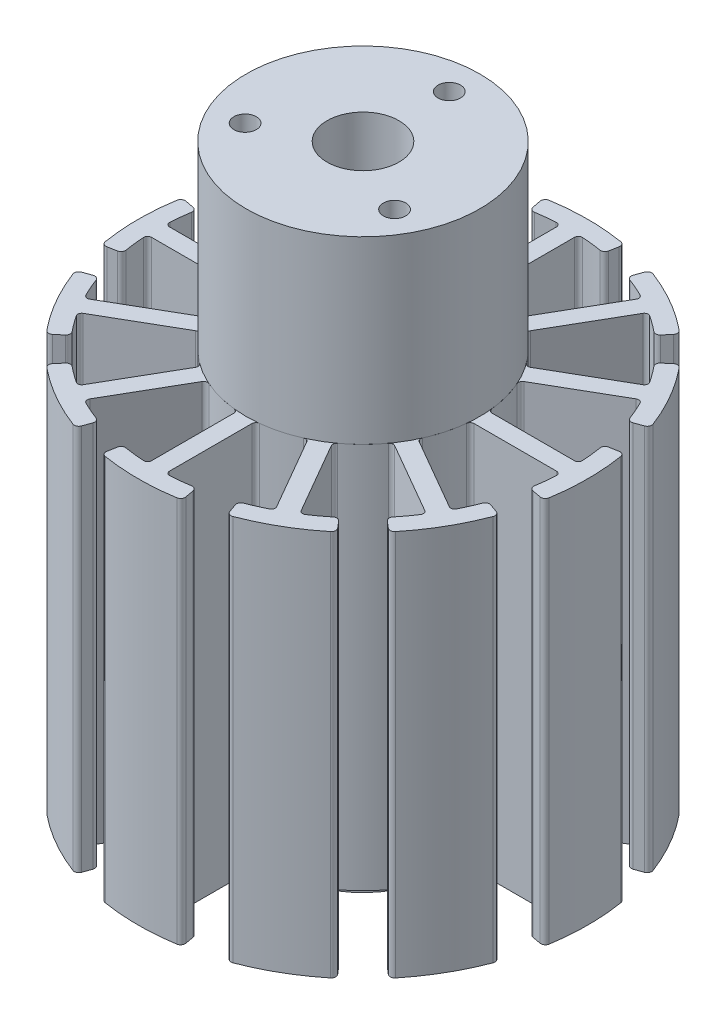
SolidWorks part; units mm, degrees
ref_plane "Front Plane" through (0, 0, 0) normal (0, 0, 1) x (1, 0, 0)
ref_plane "Top Plane" through (0, 0, 0) normal (0, 1, 0) x (1, 0, 0)
ref_plane "Right Plane" through (0, 0, 0) normal (1, 0, 0) x (0, 0, -1)
sketch "Sketch1" plane through (0, 0, 0) normal (0, 1, 0) x (1, 0, 0)
  circle A0 centre (0, 0) radius 13
  dimension "D1" = 26
extrude "Boss-Extrude1" add sketch "Sketch1" along normal blind 20
sketch "Sketch2" plane through (0, 20, 0) normal (0, 1, 0) x (1, 0, 0)
  line L0 (0, 0) -> (0, 11.9477) construction
  circle A0 centre (0, 9.6) radius 1.25
  circle A1 centre (8.3138, -4.8) radius 1.25
  circle A2 centre (-8.3138, -4.8) radius 1.25
  point P12 (0, 0)
  dimension "D1" = 9.6
  dimension "D2" = 3
extrude "Cut-Extrude1" cut sketch "Sketch2" against normal blind 5
sketch "Sketch4" plane through (0, 0, 0) normal (0, -1, 0) x (1, 0, 0)
  line L6 (0, 13) -> (0, 25) construction
  line L12 (1, 13.3636) -> (1, 22.5128)
  line L13 (-1, 13.3636) -> (-1, 22.5128)
  line L15 (4.3912, 24.0981) -> (4.2119, 23.1141)
  line L17 (-4.3912, 24.0981) -> (-4.2119, 23.1141)
  line L18 (4.1232, 22.6274) -> (4.4817, 24.595) construction
  line L19 (-4.1232, 22.6274) -> (-4.4817, 24.595) construction
  line L20 (15.8519, 18.674) -> (15.2046, 17.9114)
  line L21 (8.2462, 23.0651) -> (7.9094, 22.1233)
  line L22 (14.8845, 17.5343) -> (16.1788, 19.059) construction
  line L23 (7.7429, 21.6575) -> (8.4162, 23.5408) construction
  line L24 (7.5478, 11.0732) -> (12.1224, 18.9967)
  line L25 (5.8158, 12.0732) -> (10.3904, 19.9967)
  line L26 (23.0651, 8.2462) -> (22.1233, 7.9094)
  line L27 (18.674, 15.8519) -> (17.9114, 15.2046)
  line L28 (21.6575, 7.7429) -> (23.5408, 8.4162) construction
  line L29 (17.5343, 14.8845) -> (19.059, 16.1788) construction
  line L30 (12.0732, 5.8158) -> (19.9967, 10.3904)
  line L31 (11.0732, 7.5478) -> (18.9967, 12.1224)
  line L32 (24.0981, -4.3912) -> (23.1141, -4.2119)
  line L33 (24.0981, 4.3912) -> (23.1141, 4.2119)
  line L34 (22.6274, -4.1232) -> (24.595, -4.4817) construction
  line L35 (22.6274, 4.1232) -> (24.595, 4.4817) construction
  line L36 (13.3636, -1) -> (22.5128, -1)
  line L37 (13.3636, 1) -> (22.5128, 1)
  line L38 (18.674, -15.8519) -> (17.9114, -15.2046)
  line L39 (23.0651, -8.2462) -> (22.1233, -7.9094)
  line L40 (17.5343, -14.8845) -> (19.059, -16.1788) construction
  line L41 (21.6575, -7.7429) -> (23.5408, -8.4162) construction
  line L42 (11.0732, -7.5478) -> (18.9967, -12.1224)
  line L43 (12.0732, -5.8158) -> (19.9967, -10.3904)
  line L44 (8.2462, -23.0651) -> (7.9094, -22.1233)
  line L45 (15.8519, -18.674) -> (15.2046, -17.9114)
  line L46 (7.7429, -21.6575) -> (8.4162, -23.5408) construction
  line L47 (14.8845, -17.5343) -> (16.1788, -19.059) construction
  line L48 (5.8158, -12.0732) -> (10.3904, -19.9967)
  line L49 (7.5478, -11.0732) -> (12.1224, -18.9967)
  line L50 (-4.3912, -24.0981) -> (-4.2119, -23.1141)
  line L51 (4.3912, -24.0981) -> (4.2119, -23.1141)
  line L52 (-4.1232, -22.6274) -> (-4.4817, -24.595) construction
  line L53 (4.1232, -22.6274) -> (4.4817, -24.595) construction
  line L54 (-1, -13.3636) -> (-1, -22.5128)
  line L55 (1, -13.3636) -> (1, -22.5128)
  line L56 (-15.8519, -18.674) -> (-15.2046, -17.9114)
  line L57 (-8.2462, -23.0651) -> (-7.9094, -22.1233)
  line L58 (-14.8845, -17.5343) -> (-16.1788, -19.059) construction
  line L59 (-7.7429, -21.6575) -> (-8.4162, -23.5408) construction
  line L60 (-7.5478, -11.0732) -> (-12.1224, -18.9967)
  line L61 (-5.8158, -12.0732) -> (-10.3904, -19.9967)
  line L62 (-23.0651, -8.2462) -> (-22.1233, -7.9094)
  line L63 (-18.674, -15.8519) -> (-17.9114, -15.2046)
  line L64 (-21.6575, -7.7429) -> (-23.5408, -8.4162) construction
  line L65 (-17.5343, -14.8845) -> (-19.059, -16.1788) construction
  line L66 (-12.0732, -5.8158) -> (-19.9967, -10.3904)
  line L67 (-11.0732, -7.5478) -> (-18.9967, -12.1224)
  line L68 (-24.0981, 4.3912) -> (-23.1141, 4.2119)
  line L69 (-24.0981, -4.3912) -> (-23.1141, -4.2119)
  line L70 (-22.6274, 4.1232) -> (-24.595, 4.4817) construction
  line L71 (-22.6274, -4.1232) -> (-24.595, -4.4817) construction
  line L72 (-13.3636, 1) -> (-22.5128, 1)
  line L73 (-13.3636, -1) -> (-22.5128, -1)
  line L74 (-18.674, 15.8519) -> (-17.9114, 15.2046)
  line L75 (-23.0651, 8.2462) -> (-22.1233, 7.9094)
  line L76 (-17.5343, 14.8845) -> (-19.059, 16.1788) construction
  line L77 (-21.6575, 7.7429) -> (-23.5408, 8.4162) construction
  line L78 (-11.0732, 7.5478) -> (-18.9967, 12.1224)
  line L79 (-12.0732, 5.8158) -> (-19.9967, 10.3904)
  line L80 (-8.2462, 23.0651) -> (-7.9094, 22.1233)
  line L81 (-15.8519, 18.674) -> (-15.2046, 17.9114)
  line L82 (-7.7429, 21.6575) -> (-8.4162, 23.5408) construction
  line L83 (-14.8845, 17.5343) -> (-16.1788, 19.059) construction
  line L84 (-5.8158, 12.0732) -> (-10.3904, 19.9967)
  line L85 (-7.5478, 11.0732) -> (-12.1224, 18.9967)
  arc A0 (3.9789, 24.6813) -> (-3.9789, 24.6813) centre (0, 0) ccw
  arc A1 (3.6408, 22.71) -> (1.4693, 22.953) centre (0, 0) ccw
  arc A2 (-1.3938, 12.9251) -> (-5.2555, 11.8903) centre (0, 0) ccw
  circle A3 centre (0, 0) radius 13 construction
  arc A4 (-12.7489, 19.1433) -> (-14.8845, 17.5343) centre (0, 0) ccw
  arc A5 (-12.5, 21.6506) -> (-16.1788, 19.059) centre (0, 0) ccw
  arc A6 (-4.3912, 24.0981) -> (-3.9789, 24.6813) centre (-3.8993, 24.1877) cw
  arc A7 (-4.2119, 23.1141) -> (-3.6408, 22.71) centre (-3.72, 23.2037) ccw
  arc A8 (4.2119, 23.1141) -> (3.6408, 22.71) centre (3.72, 23.2037) cw
  arc A9 (3.9789, 24.6813) -> (4.3912, 24.0981) centre (3.8993, 24.1877) cw
  arc A10 (-1.4693, 22.953) -> (-3.6408, 22.71) centre (0, 0) ccw
  arc A11 (-1, 22.5128) -> (-1.4693, 22.953) centre (-1.4411, 22.5128) ccw
  arc A12 (1, 22.5128) -> (1.4693, 22.953) centre (1.4411, 22.5128) cw
  arc A13 (-1, 13.3636) -> (-1.3938, 12.9251) centre (-1.4411, 13.3636) cw
  arc A14 (1, 13.3636) -> (1.3938, 12.9251) centre (1.4411, 13.3636) ccw
  arc A15 (5.2555, 11.8903) -> (-5.2555, 11.8903) centre (0, 0) ccw
  arc A16 (15.7865, 19.3852) -> (8.8949, 23.3641) centre (0, 0) ccw
  arc A17 (14.5081, 17.847) -> (12.7489, 19.1433) centre (0, 0) ccw
  arc A18 (8.2462, 23.0651) -> (8.8949, 23.3641) centre (8.717, 22.8968) cw
  arc A19 (7.9094, 22.1233) -> (8.202, 21.4879) centre (8.3803, 21.955) ccw
  arc A20 (15.2046, 17.9114) -> (14.5081, 17.847) centre (14.8234, 18.235) cw
  arc A21 (15.7865, 19.3852) -> (15.8519, 18.674) centre (15.4707, 18.9975) cw
  arc A22 (10.2041, 20.6125) -> (8.202, 21.4879) centre (0, 0) ccw
  arc A23 (10.3904, 19.9967) -> (10.2041, 20.6125) centre (10.0084, 20.2172) ccw
  arc A24 (12.1224, 18.9967) -> (12.7489, 19.1433) centre (12.5044, 18.7761) cw
  arc A25 (5.8158, 12.0732) -> (5.2555, 11.8903) centre (5.4338, 12.2938) cw
  arc A26 (23.3641, 8.8949) -> (19.3852, 15.7865) centre (0, 0) ccw
  arc A27 (21.4879, 8.202) -> (20.6125, 10.2041) centre (0, 0) ccw
  arc A28 (18.674, 15.8519) -> (19.3852, 15.7865) centre (18.9975, 15.4707) cw
  arc A29 (17.9114, 15.2046) -> (17.847, 14.5081) centre (18.235, 14.8234) ccw
  arc A30 (22.1233, 7.9094) -> (21.4879, 8.202) centre (21.955, 8.3803) cw
  arc A31 (23.3641, 8.8949) -> (23.0651, 8.2462) centre (22.8968, 8.717) cw
  arc A32 (19.1433, 12.7489) -> (17.847, 14.5081) centre (0, 0) ccw
  arc A33 (18.9967, 12.1224) -> (19.1433, 12.7489) centre (18.7761, 12.5044) ccw
  arc A34 (19.9967, 10.3904) -> (20.6125, 10.2041) centre (20.2172, 10.0084) cw
  arc A35 (11.0732, 7.5478) -> (10.4965, 7.6696) centre (10.8527, 7.9298) cw
  arc A36 (24.6813, -3.9789) -> (24.6813, 3.9789) centre (0, 0) ccw
  arc A37 (22.71, -3.6408) -> (22.953, -1.4693) centre (0, 0) ccw
  arc A38 (24.0981, 4.3912) -> (24.6813, 3.9789) centre (24.1877, 3.8993) cw
  arc A39 (23.1141, 4.2119) -> (22.71, 3.6408) centre (23.2037, 3.72) ccw
  arc A40 (23.1141, -4.2119) -> (22.71, -3.6408) centre (23.2037, -3.72) cw
  arc A41 (24.6813, -3.9789) -> (24.0981, -4.3912) centre (24.1877, -3.8993) cw
  arc A42 (22.953, 1.4693) -> (22.71, 3.6408) centre (0, 0) ccw
  arc A43 (22.5128, 1) -> (22.953, 1.4693) centre (22.5128, 1.4411) ccw
  arc A44 (22.5128, -1) -> (22.953, -1.4693) centre (22.5128, -1.4411) cw
  arc A45 (13.3636, 1) -> (12.9251, 1.3938) centre (13.3636, 1.4411) cw
  arc A46 (19.3852, -15.7865) -> (23.3641, -8.8949) centre (0, 0) ccw
  arc A47 (17.847, -14.5081) -> (19.1433, -12.7489) centre (0, 0) ccw
  arc A48 (23.0651, -8.2462) -> (23.3641, -8.8949) centre (22.8968, -8.717) cw
  arc A49 (22.1233, -7.9094) -> (21.4879, -8.202) centre (21.955, -8.3803) ccw
  arc A50 (17.9114, -15.2046) -> (17.847, -14.5081) centre (18.235, -14.8234) cw
  arc A51 (19.3852, -15.7865) -> (18.674, -15.8519) centre (18.9975, -15.4707) cw
  arc A52 (20.6125, -10.2041) -> (21.4879, -8.202) centre (0, 0) ccw
  arc A53 (19.9967, -10.3904) -> (20.6125, -10.2041) centre (20.2172, -10.0084) ccw
  arc A54 (18.9967, -12.1224) -> (19.1433, -12.7489) centre (18.7761, -12.5044) cw
  arc A55 (12.0732, -5.8158) -> (11.8903, -5.2555) centre (12.2938, -5.4338) cw
  arc A56 (8.8949, -23.3641) -> (15.7865, -19.3852) centre (0, 0) ccw
  arc A57 (8.202, -21.4879) -> (10.2041, -20.6125) centre (0, 0) ccw
  arc A58 (15.8519, -18.674) -> (15.7865, -19.3852) centre (15.4707, -18.9975) cw
  arc A59 (15.2046, -17.9114) -> (14.5081, -17.847) centre (14.8234, -18.235) ccw
  arc A60 (7.9094, -22.1233) -> (8.202, -21.4879) centre (8.3803, -21.955) cw
  arc A61 (8.8949, -23.3641) -> (8.2462, -23.0651) centre (8.717, -22.8968) cw
  arc A62 (12.7489, -19.1433) -> (14.5081, -17.847) centre (0, 0) ccw
  arc A63 (12.1224, -18.9967) -> (12.7489, -19.1433) centre (12.5044, -18.7761) ccw
  arc A64 (10.3904, -19.9967) -> (10.2041, -20.6125) centre (10.0084, -20.2172) cw
  arc A65 (7.5478, -11.0732) -> (7.6696, -10.4965) centre (7.9298, -10.8527) cw
  arc A66 (-3.9789, -24.6813) -> (3.9789, -24.6813) centre (0, 0) ccw
  arc A67 (-3.6408, -22.71) -> (-1.4693, -22.953) centre (0, 0) ccw
  arc A68 (4.3912, -24.0981) -> (3.9789, -24.6813) centre (3.8993, -24.1877) cw
  arc A69 (4.2119, -23.1141) -> (3.6408, -22.71) centre (3.72, -23.2037) ccw
  arc A70 (-4.2119, -23.1141) -> (-3.6408, -22.71) centre (-3.72, -23.2037) cw
  arc A71 (-3.9789, -24.6813) -> (-4.3912, -24.0981) centre (-3.8993, -24.1877) cw
  arc A72 (1.4693, -22.953) -> (3.6408, -22.71) centre (0, 0) ccw
  arc A73 (1, -22.5128) -> (1.4693, -22.953) centre (1.4411, -22.5128) ccw
  arc A74 (-1, -22.5128) -> (-1.4693, -22.953) centre (-1.4411, -22.5128) cw
  arc A75 (1, -13.3636) -> (1.3938, -12.9251) centre (1.4411, -13.3636) cw
  arc A76 (-15.7865, -19.3852) -> (-8.8949, -23.3641) centre (0, 0) ccw
  arc A77 (-14.5081, -17.847) -> (-12.7489, -19.1433) centre (0, 0) ccw
  arc A78 (-8.2462, -23.0651) -> (-8.8949, -23.3641) centre (-8.717, -22.8968) cw
  arc A79 (-7.9094, -22.1233) -> (-8.202, -21.4879) centre (-8.3803, -21.955) ccw
  arc A80 (-15.2046, -17.9114) -> (-14.5081, -17.847) centre (-14.8234, -18.235) cw
  arc A81 (-15.7865, -19.3852) -> (-15.8519, -18.674) centre (-15.4707, -18.9975) cw
  arc A82 (-10.2041, -20.6125) -> (-8.202, -21.4879) centre (0, 0) ccw
  arc A83 (-10.3904, -19.9967) -> (-10.2041, -20.6125) centre (-10.0084, -20.2172) ccw
  arc A84 (-12.1224, -18.9967) -> (-12.7489, -19.1433) centre (-12.5044, -18.7761) cw
  arc A85 (-5.8158, -12.0732) -> (-5.2555, -11.8903) centre (-5.4338, -12.2938) cw
  arc A86 (-23.3641, -8.8949) -> (-19.3852, -15.7865) centre (0, 0) ccw
  arc A87 (-21.4879, -8.202) -> (-20.6125, -10.2041) centre (0, 0) ccw
  arc A88 (-18.674, -15.8519) -> (-19.3852, -15.7865) centre (-18.9975, -15.4707) cw
  arc A89 (-17.9114, -15.2046) -> (-17.847, -14.5081) centre (-18.235, -14.8234) ccw
  arc A90 (-22.1233, -7.9094) -> (-21.4879, -8.202) centre (-21.955, -8.3803) cw
  arc A91 (-23.3641, -8.8949) -> (-23.0651, -8.2462) centre (-22.8968, -8.717) cw
  arc A92 (-19.1433, -12.7489) -> (-17.847, -14.5081) centre (0, 0) ccw
  arc A93 (-18.9967, -12.1224) -> (-19.1433, -12.7489) centre (-18.7761, -12.5044) ccw
  arc A94 (-19.9967, -10.3904) -> (-20.6125, -10.2041) centre (-20.2172, -10.0084) cw
  arc A95 (-11.0732, -7.5478) -> (-10.4965, -7.6696) centre (-10.8527, -7.9298) cw
  arc A96 (-24.6813, 3.9789) -> (-24.6813, -3.9789) centre (0, 0) ccw
  arc A97 (-22.71, 3.6408) -> (-22.953, 1.4693) centre (0, 0) ccw
  arc A98 (-24.0981, -4.3912) -> (-24.6813, -3.9789) centre (-24.1877, -3.8993) cw
  arc A99 (-23.1141, -4.2119) -> (-22.71, -3.6408) centre (-23.2037, -3.72) ccw
  arc A100 (-23.1141, 4.2119) -> (-22.71, 3.6408) centre (-23.2037, 3.72) cw
  arc A101 (-24.6813, 3.9789) -> (-24.0981, 4.3912) centre (-24.1877, 3.8993) cw
  arc A102 (-22.953, -1.4693) -> (-22.71, -3.6408) centre (0, 0) ccw
  arc A103 (-22.5128, -1) -> (-22.953, -1.4693) centre (-22.5128, -1.4411) ccw
  arc A104 (-22.5128, 1) -> (-22.953, 1.4693) centre (-22.5128, 1.4411) cw
  arc A105 (-13.3636, -1) -> (-12.9251, -1.3938) centre (-13.3636, -1.4411) cw
  arc A106 (-19.3852, 15.7865) -> (-23.3641, 8.8949) centre (0, 0) ccw
  arc A107 (-17.847, 14.5081) -> (-19.1433, 12.7489) centre (0, 0) ccw
  arc A108 (-23.0651, 8.2462) -> (-23.3641, 8.8949) centre (-22.8968, 8.717) cw
  arc A109 (-22.1233, 7.9094) -> (-21.4879, 8.202) centre (-21.955, 8.3803) ccw
  arc A110 (-17.9114, 15.2046) -> (-17.847, 14.5081) centre (-18.235, 14.8234) cw
  arc A111 (-19.3852, 15.7865) -> (-18.674, 15.8519) centre (-18.9975, 15.4707) cw
  arc A112 (-20.6125, 10.2041) -> (-21.4879, 8.202) centre (0, 0) ccw
  arc A113 (-19.9967, 10.3904) -> (-20.6125, 10.2041) centre (-20.2172, 10.0084) ccw
  arc A114 (-18.9967, 12.1224) -> (-19.1433, 12.7489) centre (-18.7761, 12.5044) cw
  arc A115 (-12.0732, 5.8158) -> (-11.8903, 5.2555) centre (-12.2938, 5.4338) cw
  arc A116 (-8.8949, 23.3641) -> (-15.7865, 19.3852) centre (0, 0) ccw
  arc A117 (-8.202, 21.4879) -> (-10.2041, 20.6125) centre (0, 0) ccw
  arc A118 (-15.8519, 18.674) -> (-15.7865, 19.3852) centre (-15.4707, 18.9975) cw
  arc A119 (-15.2046, 17.9114) -> (-14.5081, 17.847) centre (-14.8234, 18.235) ccw
  arc A120 (-7.9094, 22.1233) -> (-8.202, 21.4879) centre (-8.3803, 21.955) cw
  arc A121 (-8.8949, 23.3641) -> (-8.2462, 23.0651) centre (-8.717, 22.8968) cw
  arc A122 (-12.7489, 19.1433) -> (-14.5081, 17.847) centre (0, 0) ccw
  arc A123 (-12.1224, 18.9967) -> (-12.7489, 19.1433) centre (-12.5044, 18.7761) ccw
  arc A124 (-10.3904, 19.9967) -> (-10.2041, 20.6125) centre (-10.0084, 20.2172) cw
  arc A125 (-7.5478, 11.0732) -> (-7.6696, 10.4965) centre (-7.9298, 10.8527) cw
  arc A126 (16.1788, 19.059) -> (12.5, 21.6506) centre (0, 0) ccw
  arc A127 (14.8845, 17.5343) -> (12.7489, 19.1433) centre (0, 0) ccw
  arc A128 (23.5408, 8.4162) -> (19.059, 16.1788) centre (0, 0) ccw
  arc A129 (5.2555, 11.8903) -> (1.3938, 12.9251) centre (0, 0) ccw
  arc A130 (24.595, -4.4817) -> (24.595, 4.4817) centre (0, 0) ccw
  arc A131 (22.6274, -4.1232) -> (22.953, -1.4693) centre (0, 0) ccw
  arc A132 (19.059, -16.1788) -> (23.5408, -8.4162) centre (0, 0) ccw
  arc A133 (17.5343, -14.8845) -> (19.1433, -12.7489) centre (0, 0) ccw
  arc A134 (8.4162, -23.5408) -> (16.1788, -19.059) centre (0, 0) ccw
  arc A135 (7.7429, -21.6575) -> (10.2041, -20.6125) centre (0, 0) ccw
  arc A136 (-4.4817, -24.595) -> (4.4817, -24.595) centre (0, 0) ccw
  arc A137 (-4.1232, -22.6274) -> (-1.4693, -22.953) centre (0, 0) ccw
  arc A138 (-16.1788, -19.059) -> (-8.4162, -23.5408) centre (0, 0) ccw
  arc A139 (-14.8845, -17.5343) -> (-12.7489, -19.1433) centre (0, 0) ccw
  arc A140 (-23.5408, -8.4162) -> (-19.059, -16.1788) centre (0, 0) ccw
  arc A141 (-21.6575, -7.7429) -> (-20.6125, -10.2041) centre (0, 0) ccw
  arc A142 (-24.595, 4.4817) -> (-24.595, -4.4817) centre (0, 0) ccw
  arc A143 (-22.6274, 4.1232) -> (-22.953, 1.4693) centre (0, 0) ccw
  arc A144 (-19.059, 16.1788) -> (-23.5408, 8.4162) centre (0, 0) ccw
  arc A145 (-17.5343, 14.8845) -> (-19.1433, 12.7489) centre (0, 0) ccw
  arc A146 (7.5478, 11.0732) -> (7.6696, 10.4965) centre (7.9298, 10.8527) ccw
  arc A147 (12.0732, 5.8158) -> (11.8903, 5.2555) centre (12.2938, 5.4338) ccw
  arc A148 (13.3636, -1) -> (12.9251, -1.3938) centre (13.3636, -1.4411) ccw
  arc A149 (11.0732, -7.5478) -> (10.4965, -7.6696) centre (10.8527, -7.9298) ccw
  arc A150 (5.8158, -12.0732) -> (5.2555, -11.8903) centre (5.4338, -12.2938) ccw
  arc A151 (-1, -13.3636) -> (-1.3938, -12.9251) centre (-1.4411, -13.3636) ccw
  arc A152 (-7.5478, -11.0732) -> (-7.6696, -10.4965) centre (-7.9298, -10.8527) ccw
  arc A153 (-12.0732, -5.8158) -> (-11.8903, -5.2555) centre (-12.2938, -5.4338) ccw
  arc A154 (-13.3636, 1) -> (-12.9251, 1.3938) centre (-13.3636, 1.4411) ccw
  arc A155 (-11.0732, 7.5478) -> (-10.4965, 7.6696) centre (-10.8527, 7.9298) ccw
  arc A156 (-5.8158, 12.0732) -> (-5.2555, 11.8903) centre (-5.4338, 12.2938) ccw
  arc A157 (-20.6125, 10.2041) -> (-21.6575, 7.7429) centre (0, 0) ccw
  arc A158 (-22.953, -1.4693) -> (-22.6274, -4.1232) centre (0, 0) ccw
  arc A159 (-19.1433, -12.7489) -> (-17.5343, -14.8845) centre (0, 0) ccw
  arc A160 (-10.2041, -20.6125) -> (-7.7429, -21.6575) centre (0, 0) ccw
  arc A161 (1.4693, -22.953) -> (4.1232, -22.6274) centre (0, 0) ccw
  arc A162 (12.7489, -19.1433) -> (14.8845, -17.5343) centre (0, 0) ccw
  arc A163 (20.6125, -10.2041) -> (21.6575, -7.7429) centre (0, 0) ccw
  arc A164 (22.953, 1.4693) -> (22.6274, 4.1232) centre (0, 0) ccw
  arc A165 (19.1433, 12.7489) -> (17.5343, 14.8845) centre (0, 0) ccw
  arc A166 (10.4965, 7.6696) -> (7.6696, 10.4965) centre (0, 0) ccw
  arc A167 (10.4965, 7.6696) -> (7.6696, 10.4965) centre (0, 0) ccw
  arc A168 (12.9251, 1.3938) -> (11.8903, 5.2555) centre (0, 0) ccw
  arc A169 (12.9251, 1.3938) -> (11.8903, 5.2555) centre (0, 0) ccw
  arc A170 (11.8903, -5.2555) -> (12.9251, -1.3938) centre (0, 0) ccw
  arc A171 (11.8903, -5.2555) -> (12.9251, -1.3938) centre (0, 0) ccw
  arc A172 (7.6696, -10.4965) -> (10.4965, -7.6696) centre (0, 0) ccw
  arc A173 (7.6696, -10.4965) -> (10.4965, -7.6696) centre (0, 0) ccw
  arc A174 (1.3938, -12.9251) -> (5.2555, -11.8903) centre (0, 0) ccw
  arc A175 (1.3938, -12.9251) -> (5.2555, -11.8903) centre (0, 0) ccw
  arc A176 (-5.2555, -11.8903) -> (-1.3938, -12.9251) centre (0, 0) ccw
  arc A177 (-5.2555, -11.8903) -> (-1.3938, -12.9251) centre (0, 0) ccw
  arc A178 (-10.4965, -7.6696) -> (-7.6696, -10.4965) centre (0, 0) ccw
  arc A179 (-10.4965, -7.6696) -> (-7.6696, -10.4965) centre (0, 0) ccw
  arc A180 (-12.9251, -1.3938) -> (-11.8903, -5.2555) centre (0, 0) ccw
  arc A181 (-12.9251, -1.3938) -> (-11.8903, -5.2555) centre (0, 0) ccw
  arc A182 (-11.8903, 5.2555) -> (-12.9251, 1.3938) centre (0, 0) ccw
  arc A183 (-11.8903, 5.2555) -> (-12.9251, 1.3938) centre (0, 0) ccw
  arc A184 (-7.6696, 10.4965) -> (-10.4965, 7.6696) centre (0, 0) ccw
  arc A185 (-7.6696, 10.4965) -> (-10.4965, 7.6696) centre (0, 0) ccw
  point P18 (0, 0)
  point P44 (-1, 22.9783)
  point P48 (-1, 12.9615)
  point P340 (0, 0)
  point P375 (0, 0)
  circle M2 centre (0, 0) radius 13
  dimension "D2" = 2
  dimension "D3" = 26
  dimension "D7" = 0.5
  dimension "D8" = 0.4411
  dimension "D9" = 0.4411
  dimension "D4" = 1
  dimension "D5" = 1
  dimension "D6" = 4.5
  dimension "D10" = 12
  dimension "D11" = 12
extrude "Boss-Extrude2" add sketch "Sketch4" along normal blind 43 separate body contours A14 L12 A12 A1 A8 L15 A9 A0 A6 L17 A7 A10 A11 L13 A13 M2 | M2 | A147 L30 A34 A27 A30 L26 A31 A26 A28 L27 A29 A32 A33 L31 A35 M2 | A148 L36 A44 A37 A40 L32 A41 A36 A38 L33 A39 A42 A43 L37 A45 M2 | A146 L24 A24 A17 A20 L20 A21 A16 A18 L21 A19 A22 A23 L25 A25 M2 | A156 L84 A124 A117 A120 L80 A121 A116 A5 A118 L81 A119 A4 A123 L85 A125 M2 | A155 L78 A114 A107 A110 L74 A111 A106 A108 L75 A109 A112 A113 L79 A115 M2 | A154 L72 A104 A97 A100 L68 A101 A96 A98 L69 A99 A102 A103 L73 A105 M2 | A153 L66 A94 A87 A90 L62 A91 A86 A88 L63 A89 A92 A93 L67 A95 M2 | A152 L60 A84 A77 A80 L56 A81 A76 A78 L57 A79 A82 A83 L61 A85 M2 | A150 L48 A64 A57 A60 L44 A61 A56 A58 L45 A59 A62 A63 L49 A65 M2 | A151 L54 A74 A67 A70 L50 A71 A66 A68 L51 A69 A72 A73 L55 A75 M2 | A149 L42 A54 A47 A50 L38 A51 A46 A48 L39 A49 A52 A53 L43 A55 M2
sketch "Sketch5" plane through (0, 0, 0) normal (0, 0, 1) x (1, 0, 0)
  line L0 (0, 0) -> (0, -37.4719)
sketch "Sketch6" plane through (0, -43, 0) normal (0, -1, 0) x (-1, 0, 0)
  circle A0 centre (0, 0) radius 9
  dimension "D1" = 18
extrude "Boss-Extrude3" add sketch "Sketch6" along normal blind 3
sketch "Sketch7" plane through (0, -46, 0) normal (0, -1, 0) x (-1, 0, 0)
  circle A0 centre (0, 0) radius 6
  dimension "D1" = 12
extrude "Cut-Extrude2" cut sketch "Sketch7" against normal blind 3
sketch "Sketch8" plane through (0, -43, 0) normal (0, -1, 0) x (-1, 0, 0)
  circle A0 centre (0, 0) radius 4
extrude "Cut-Extrude3" cut sketch "Sketch8" against normal through all
